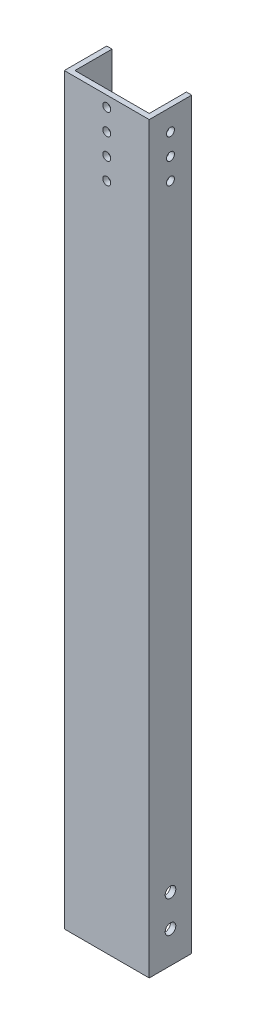
SolidWorks part; units mm, degrees
ref_plane "Front Plane" through (0, 0, 0) normal (0, 0, 1) x (1, 0, 0)
ref_plane "Top Plane" through (0, 0, 0) normal (0, 1, 0) x (1, 0, 0)
ref_plane "Right Plane" through (0, 0, 0) normal (1, 0, 0) x (0, 0, -1)
sketch "Sketch1" plane through (0, 0, 0) normal (0, 1, 0) x (1, 0, 0)
  line L0 (0, 0) -> (50.8, 0)
  line L1 (50.8, 0) -> (50.8, 25.4)
  line L2 (50.8, 25.4) -> (47.625, 25.4)
  line L3 (47.625, 25.4) -> (47.625, 3.175)
  line L4 (47.625, 3.175) -> (3.175, 3.175)
  line L5 (3.175, 3.175) -> (3.175, 25.4)
  line L6 (3.175, 25.4) -> (0, 25.4)
  line L7 (0, 25.4) -> (0, 0)
  dimension "D1" = 25.4
  dimension "D2" = 50.8
  dimension "D3" = 3.175
  dimension "D4" = 3.175
  dimension "D5" = 3.175
  dimension "D6" = 25.4
extrude "Boss-Extrude1" add sketch "Sketch1" along normal blind 444.5
sketch "Sketch2" plane through (50.8, 0, 0) normal (1, 0, 0) x (0, 0, -1)
  line L0 (0, 444.5) -> (0, 0) construction
  line L2 (0, 0) -> (25.4, 0) construction
  line L3 (0, 444.5) -> (25.4, 444.5) construction
  line L4 (25.4, 444.5) -> (25.4, 0) construction
  circle A0 centre (12.7, 38.1) radius 3.175
  circle A1 centre (12.7, 19.05) radius 3.175
  circle A2 centre (12.7, 406.4) radius 2.3813
  circle A3 centre (12.7, 419.1) radius 2.3813
  circle A4 centre (12.7, 431.8) radius 2.3813
  point P14 (12.7, 12.7)
  point P15 (12.7, 0)
  dimension "D1" = 6.35
  dimension "D2" = 19.05
  dimension "D3" = 12.7
  dimension "D4" = 19.05
  dimension "D5" = 4.7625
  dimension "D6" = 12.7
  dimension "D7" = 12.7
  dimension "D8" = 0
  dimension "D9" = 12.7
  dimension "D10" = 0
  dimension "D11" = 12.7
extrude "Cut-Extrude1" cut sketch "Sketch2" against normal through all
sketch "Sketch3" plane through (0, 0, 0) normal (0, 0, 1) x (1, 0, 0)
  line L3 (0, 444.5) -> (0, 0) construction
  line L5 (0, 444.5) -> (50.8, 444.5) construction
  circle A0 centre (25.4, 438.15) radius 2.3813
  circle A1 centre (25.4, 425.45) radius 2.3813
  circle A2 centre (25.4, 412.75) radius 2.3813
  circle A3 centre (25.4, 400.05) radius 2.3813
  dimension "D1" = 4.7625
  dimension "D2" = 25.4
  dimension "D3" = 6.35
  dimension "D4" = 4.7625
  dimension "D5" = 4.7625
  dimension "D6" = 4.7625
  dimension "D7" = 19.05
  dimension "D8" = 31.75
  dimension "D9" = 44.45
extrude "Cut-Extrude2" cut sketch "Sketch3" against normal through all
equation "\"D6@Sketch1\"=\"D1@Sketch1\""
